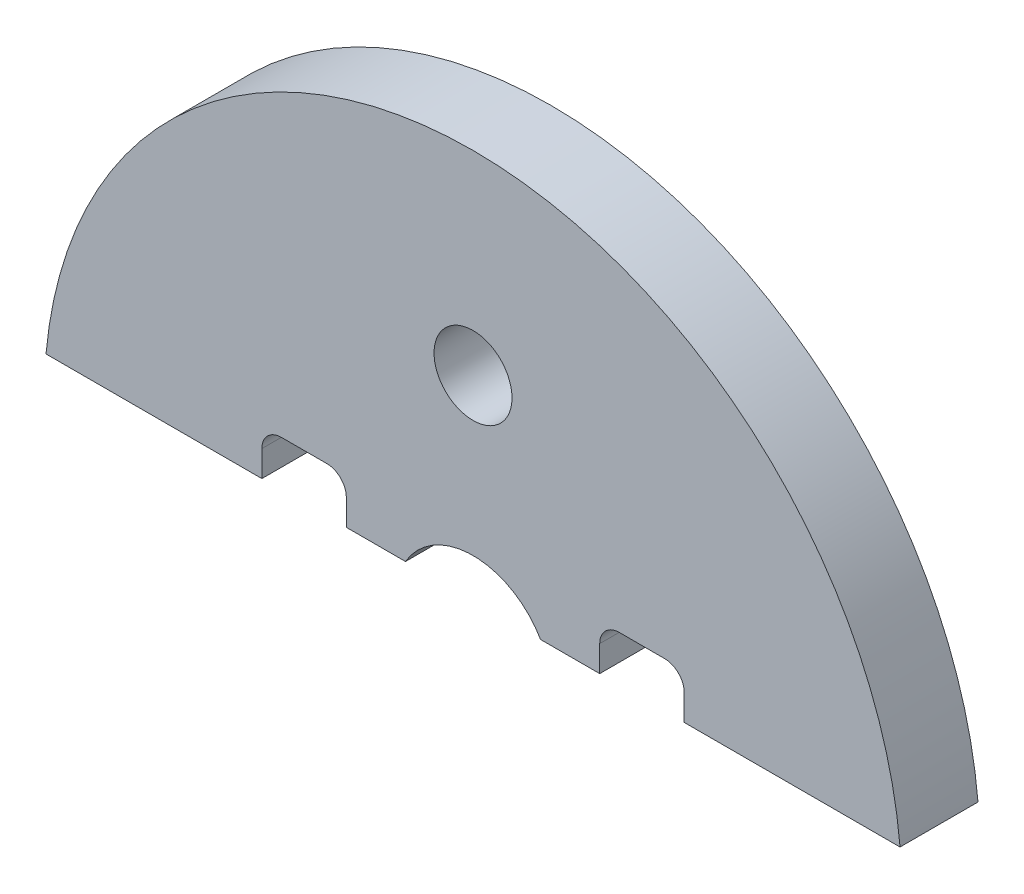
SolidWorks part; units mm, degrees
ref_plane "Alzado" through (0, 0, 0) normal (0, 0, 1) x (1, 0, 0)
ref_plane "Planta" through (0, 0, 0) normal (0, 1, 0) x (1, 0, 0)
ref_plane "Vista lateral" through (0, 0, 0) normal (1, 0, 0) x (0, 0, -1)
sketch "Model" plane through (0, 0, 0) normal (0, 0, 1) x (1, 0, 0)
  line L0 (223.1228, 245.202) -> (221.3728, 245.202)
  line L1 (208.3728, 245.202) -> (210.1228, 245.202)
  line L2 (223.8728, 243.452) -> (232.1795, 243.452)
  line L3 (223.8728, 243.452) -> (223.8728, 244.452)
  line L4 (220.6228, 244.452) -> (220.6228, 243.452)
  line L5 (210.8728, 244.452) -> (210.8728, 243.452)
  line L6 (207.6228, 243.452) -> (207.6228, 244.452)
  line L7 (199.3161, 243.452) -> (207.6228, 243.452)
  line L8 (210.8728, 243.452) -> (213.1497, 243.452)
  line L9 (218.3459, 243.452) -> (220.6228, 243.452)
  circle A0 centre (215.7478, 250.952) radius 1.5
  arc A1 (221.3728, 245.202) -> (220.6228, 244.452) centre (221.3728, 244.452) ccw
  arc A2 (223.8728, 244.452) -> (223.1228, 245.202) centre (223.1228, 244.452) ccw
  arc A3 (210.8728, 244.452) -> (210.1228, 245.202) centre (210.1228, 244.452) ccw
  arc A4 (208.3728, 245.202) -> (207.6228, 244.452) centre (208.3728, 244.452) ccw
  arc A5 (232.1795, 243.452) -> (199.3161, 243.452) centre (215.7478, 241.952) ccw
  arc A6 (218.3459, 243.452) -> (213.1497, 243.452) centre (215.7478, 241.952) ccw
extrude "Saliente-Extruir1" add sketch "Model" along normal blind 3
